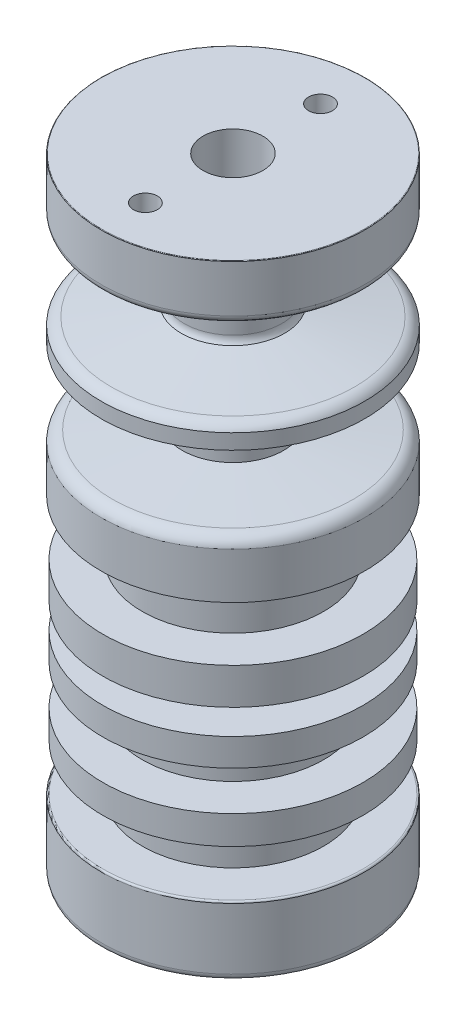
SolidWorks part; units mm, degrees
ref_plane "Alzado" through (0, 0, 0) normal (0, 0, 1) x (1, 0, 0)
ref_plane "Planta" through (0, 0, 0) normal (0, 1, 0) x (1, 0, 0)
ref_plane "Vista lateral" through (0, 0, 0) normal (1, 0, 0) x (0, 0, -1)
sketch "Croquis1" plane through (0, 0, 0) normal (0, 0, 1) x (1, 0, 0)
  line L0 (0, 0) -> (0, 43.0446) construction
  line L1 (0, 43.0446) -> (0, -121.9554) construction
  line L2 (0, 43.0446) -> (34.8584, 43.0446)
  line L3 (35, 42.903) -> (35, 30.366)
  line L4 (32.9644, 28.3304) -> (12.9858, 28.3304)
  line L5 (12.9858, 28.3304) -> (12.9858, 10.4062)
  line L6 (13.718, 8.5125) -> (32.3097, 5.486)
  line L7 (35, 3.5416) -> (35, -0.4901)
  line L8 (13.4687, -0.4901) -> (35, -0.4901)
  line L9 (13.4687, -0.4901) -> (13.4687, -18.5388)
  line L10 (13.4687, -18.5388) -> (31.9792, -20.5132)
  line L11 (35, -23.2242) -> (35, -35.5011)
  line L12 (24.0861, -91.9234) -> (34.5383, -91.9234)
  line L13 (24.0861, -91.9234) -> (24.0861, -104.2217)
  line L14 (24.0861, -104.2217) -> (34.5383, -104.2217)
  line L15 (35, -104.6833) -> (35, -120.9509)
  line L16 (34.7378, -121.991) -> (0, -121.9554)
  line L17 (0, 43.0446) -> (0, -121.9554)
  line L18 (34.5383, -91.9234) -> (34.5383, -84.3501)
  line L19 (35, -35.5011) -> (24.0861, -35.5011)
  line L20 (24.0861, -35.5011) -> (24.0861, -50.2633)
  line L21 (34.5383, -84.3501) -> (24.0861, -84.3501)
  line L22 (24.0861, -73.9073) -> (34.5383, -73.9073)
  line L23 (34.5383, -73.9073) -> (34.5383, -66.6171)
  line L24 (34.5383, -66.6171) -> (24.0861, -66.6171)
  line L25 (24.0861, -59.9179) -> (34.5383, -59.9179)
  line L26 (34.5383, -59.9179) -> (34.5383, -50.2633)
  line L27 (34.5383, -50.2633) -> (24.0861, -50.2633)
  line L28 (24.0861, -73.9073) -> (24.0861, -84.3501)
  line L29 (24.0861, -59.9179) -> (24.0861, -66.6171)
  arc A0 (34.8584, 43.0446) -> (35, 42.903) centre (34.8584, 42.903) cw
  arc A1 (35, 30.366) -> (32.9644, 28.3304) centre (32.9644, 30.366) cw
  arc A2 (12.9858, 10.4062) -> (13.718, 8.5125) centre (15.8008, 10.4062) ccw
  arc A3 (32.3097, 5.486) -> (35, 3.5416) centre (31.7144, 1.829) cw
  arc A6 (31.9792, -20.5132) -> (35, -23.2242) centre (31.6114, -23.9615) cw
  arc A8 (34.5383, -104.2217) -> (35, -104.6833) centre (34.5383, -104.6833) cw
  arc A9 (35, -120.9509) -> (34.7378, -121.991) centre (32.8058, -120.9509) cw
  dimension "D1" = 165
  dimension "D2" = 34.8584
  dimension "D3" = 35
  dimension "D4" = 35
  dimension "D5" = 35
revolve "Revolución3" add sketch "Croquis1" angle 360 about L17
sketch "Croquis2" plane through (0, 43.0446, 0) normal (0, 1, 0) x (1, 0, 0)
  line L0 (0.2449, 23) -> (-0.2449, -23) construction
  line L1 (-0.2449, -23) -> (0, 0) construction
  line L2 (0, 0) -> (11.2888, 0) construction
  circle A0 centre (-0.2449, -23) radius 3.175
  circle A2 centre (0.2449, 23) radius 3.175
  point P4 (0, 0)
  point P7 (0, 0)
  dimension "D3" = 6.35
  dimension "D5" = 6.35
  dimension "D1" = 46
extrude "Cortar-Extruir2" cut sketch "Croquis2" against normal blind 12
sketch "Croquis5" plane through (0, -104.2217, 0) normal (0, 1, 0) x (1, 0, 0)
  circle A0 centre (0.0979, 0) radius 7.9375
  dimension "D1" = 15.875
extrude "Cortar-Extruir3" cut sketch "Croquis5" against normal blind 18
sketch "Croquis6" plane through (0, 43.0446, 0) normal (0, 1, 0) x (1, 0, 0)
  circle A0 centre (0, 0) radius 7.9375
  dimension "D1" = 15.875
extrude "Cortar-Extruir4" cut sketch "Croquis6" against normal blind 12
ref_plane "Plano1" through (0, 0, 0) normal (1, 0, 0) x (0, 0, -1)
ref_plane "Plano2" through (0, 0, 0) normal (0, 0, 1) x (1, 0, 0)
sketch "Croquis7" plane through (0, 43.0446, 0) normal (0, 1, 0) x (1, 0, 0)
  circle A0 centre (0, 0) radius 30.5
  circle A1 centre (0, 0) radius 35.1502
  dimension "D1" = 61
